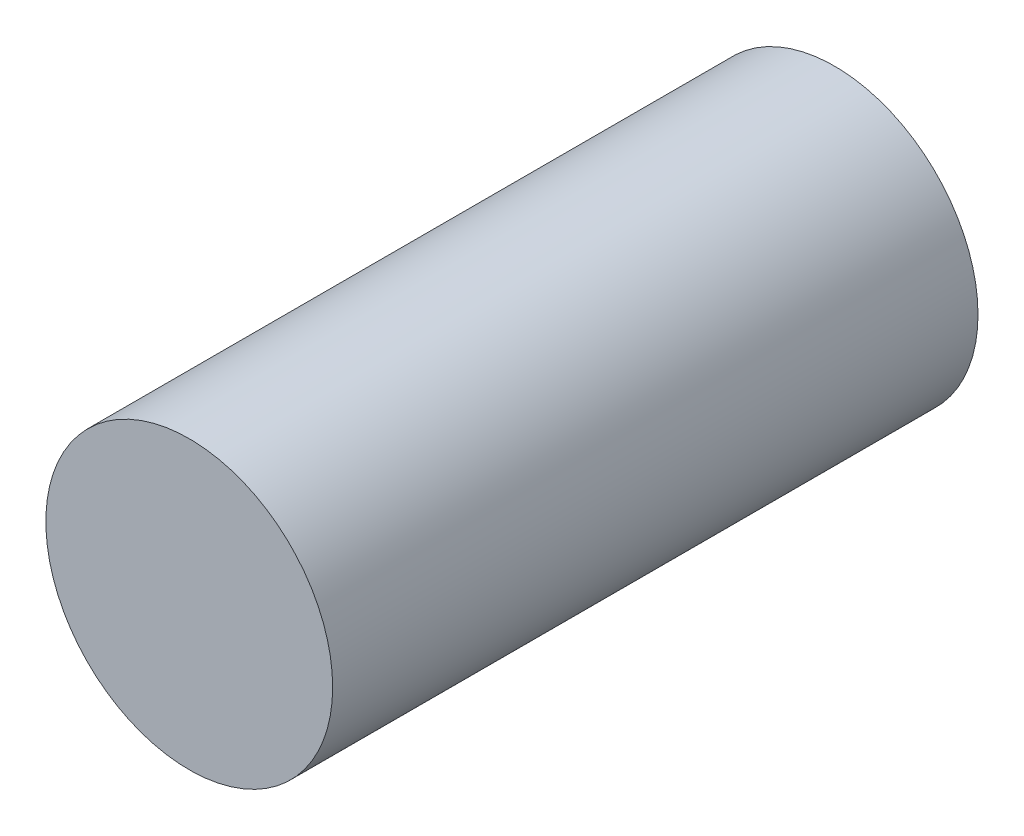
SolidWorks part; units mm, degrees
ref_plane "前视基准面" through (0, 0, 0) normal (0, 0, 1) x (1, 0, 0)
ref_plane "上视基准面" through (0, 0, 0) normal (0, 1, 0) x (1, 0, 0)
ref_plane "右视基准面" through (0, 0, 0) normal (1, 0, 0) x (0, 0, -1)
sketch "草图1" plane through (0, 0, 0) normal (0, 0, 1) x (1, 0, 0)
  circle A0 centre (21.5943, 0) radius 20
extrude "凸台-拉伸1" add sketch "草图1" against normal up to surface (90 mm away)
